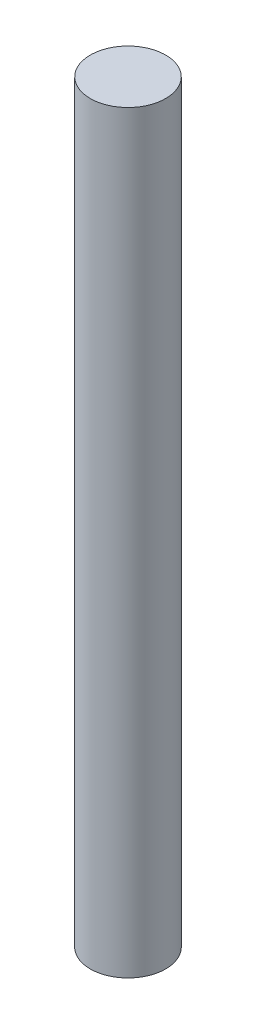
SolidWorks part; units mm, degrees
ref_plane "Front Plane" through (0, 0, 0) normal (0, 0, 1) x (1, 0, 0)
ref_plane "Top Plane" through (0, 0, 0) normal (0, 1, 0) x (1, 0, 0)
ref_plane "Right Plane" through (0, 0, 0) normal (1, 0, 0) x (0, 0, -1)
sketch "Sketch1" plane through (0, 0, 0) normal (0, 1, 0) x (1, 0, 0)
  circle A0 centre (0, 0) radius 1
  dimension "D1" = 2
extrude "Boss-Extrude1" add sketch "Sketch1" along normal blind 20
